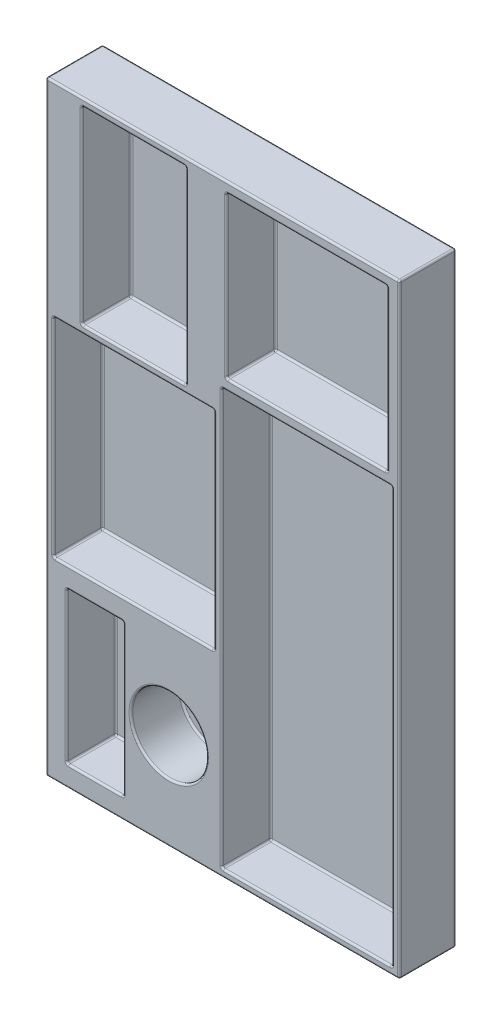
SolidWorks part; units mm, degrees
ref_plane "Front Plane" through (0, 0, 0) normal (0, 0, 1) x (1, 0, 0)
ref_plane "Top Plane" through (0, 0, 0) normal (0, 1, 0) x (1, 0, 0)
ref_plane "Right Plane" through (0, 0, 0) normal (1, 0, 0) x (0, 0, -1)
sketch "Sketch1" plane through (0, 0, 0) normal (0, 0, 1) x (1, 0, 0)
  line L1 (93.5, -160) -> (-93.5, -160)
  line L2 (93.5, -160) -> (93.5, 160)
  line L3 (93.5, 160) -> (-93.5, 160)
  line L4 (-93.5, -160) -> (-93.5, 160)
  line L5 (93.5, -160) -> (-93.5, 160) construction
  line L6 (93.5, 160) -> (-93.5, -160) construction
  point P0 (0, 0)
  dimension "D1" = 320
  dimension "D2" = 187
extrude "Boss-Extrude1" add sketch "Sketch1" along normal blind 30
sketch "Sketch3" plane through (0, 0, 30) normal (0, 0, 1) x (1, 0, 0)
  line L0 (-93.5, -160) -> (93.5, -160) construction
  line L1 (-0.5, 64) -> (89.5, 64)
  line L2 (-0.5, 64) -> (-0.5, -156)
  line L3 (-0.5, -156) -> (89.5, -156)
  line L4 (89.5, 64) -> (89.5, -156)
  line L5 (93.5, -160) -> (93.5, 160) construction
  dimension "D1" = 90
  dimension "D2" = 220
  dimension "D3" = 4
  dimension "D4" = 4
extrude "Cut-Extrude1" cut sketch "Sketch3" against normal blind 26
sketch "Sketch4" plane through (0, 0, 30) normal (0, 0, 1) x (1, 0, 0)
  line L1 (2, 154.5) -> (87, 154.5)
  line L2 (2, 154.5) -> (2, 69.5)
  line L3 (2, 69.5) -> (87, 69.5)
  line L4 (87, 154.5) -> (87, 69.5)
  line L5 (93.5, 160) -> (-93.5, 160) construction
  line L8 (-0.5, 64) -> (-0.5, -156) construction
  dimension "D1" = 85
  dimension "D2" = 85
  dimension "D3" = 5.5
  dimension "D4" = 2.5
extrude "Cut-Extrude2" cut sketch "Sketch4" against normal blind 26
sketch "Sketch5" plane through (0, 0, 30) normal (0, 0, 1) x (1, 0, 0)
  line L0 (-0.5, 64) -> (-0.5, -156) construction
  line L1 (-74.5, 156) -> (-19.5, 156)
  line L2 (-74.5, 156) -> (-74.5, 56)
  line L3 (-74.5, 56) -> (-19.5, 56)
  line L4 (-19.5, 156) -> (-19.5, 56)
  line L5 (93.5, 160) -> (-93.5, 160) construction
  dimension "D1" = 55
  dimension "D2" = 100
  dimension "D3" = 19
  dimension "D4" = 4
extrude "Cut-Extrude3" cut sketch "Sketch5" against normal blind 26
sketch "Sketch6" plane through (0, 0, 30) normal (0, 0, 1) x (1, 0, 0)
  line L0 (-74.5, 56) -> (-19.5, 56) construction
  line L1 (-89.5, 52) -> (-4.5, 52)
  line L2 (-89.5, 52) -> (-89.5, -58)
  line L3 (-89.5, -58) -> (-4.5, -58)
  line L4 (-4.5, 52) -> (-4.5, -58)
  line L5 (-0.5, 64) -> (-0.5, -156) construction
  dimension "D1" = 85
  dimension "D2" = 110
  dimension "D3" = 4
  dimension "D4" = 4
extrude "Cut-Extrude4" cut sketch "Sketch6" against normal blind 26
sketch "Sketch7" plane through (0, 0, 30) normal (0, 0, 1) x (1, 0, 0)
  line L4 (-0.5, 64) -> (-0.5, -156) construction
  line L5 (-89.5, -58) -> (-4.5, -58) construction
  line L7 (-82.5, -69) -> (-52.5, -69)
  line L8 (-82.5, -69) -> (-82.5, -149)
  line L9 (-82.5, -149) -> (-52.5, -149)
  line L10 (-52.5, -69) -> (-52.5, -149)
  circle A0 centre (-28.5, -109) radius 20
  dimension "D1" = 40
  dimension "D2" = 28
  dimension "D3" = 51
  dimension "D4" = 30
  dimension "D5" = 80
  dimension "D6" = 11
  dimension "D7" = 24
extrude "Cut-Extrude6" cut sketch "Sketch7" against normal blind 26
fillet "Fillet1" radius 1 74 edges at (-82.5, -109, 30) (-67.5, -149, 30) (-52.5, -109, 30) (-67.5, -69, 30) (-82.5, -109, 4) (-67.5, -149, 4) (-52.5, -109, 4) (-67.5, -69, 4) (-82.5, -149, 17) (-52.5, -149, 17) (-52.5, -69, 17) (-82.5, -69, 17) (-8.5, -109, 30) (-8.5, -109, 4) (-89.5, -3, 30) (-47, -58, 30) (-4.5, -3, 30) (-47, 52, 30) (-89.5, -3, 4) (-47, -58, 4) (-4.5, -3, 4) (-47, 52, 4) (-89.5, -58, 17) (-4.5, -58, 17) (-4.5, 52, 17) (-89.5, 52, 17) (-74.5, 106, 30) (-47, 56, 30) (-19.5, 106, 30) (-47, 156, 30) (-74.5, 106, 4) (-47, 56, 4) (-19.5, 106, 4) (-47, 156, 4) (-74.5, 56, 17) (-19.5, 56, 17) (-19.5, 156, 17) (-74.5, 156, 17) (2, 112, 30) (44.5, 69.5, 30) (87, 112, 30) (44.5, 154.5, 30) (2, 112, 4) (44.5, 69.5, 4) (87, 112, 4) (44.5, 154.5, 4) (2, 69.5, 17) (87, 69.5, 17) (87, 154.5, 17) (2, 154.5, 17) (-0.5, -46, 30) (44.5, -156, 30) (89.5, -46, 30) (44.5, 64, 30) (-0.5, -46, 4) (44.5, -156, 4) (89.5, -46, 4) (44.5, 64, 4) (-0.5, -156, 17) (89.5, -156, 17) (89.5, 64, 17) (-0.5, 64, 17) (-93.5, 0, 0) (0, -160, 0) (93.5, 0, 0) (0, 160, 0) (-93.5, 0, 30) (0, -160, 30) (93.5, 0, 30) (0, 160, 30) (-93.5, 160, 15) (93.5, 160, 15) (93.5, -160, 15) (-93.5, -160, 15)
